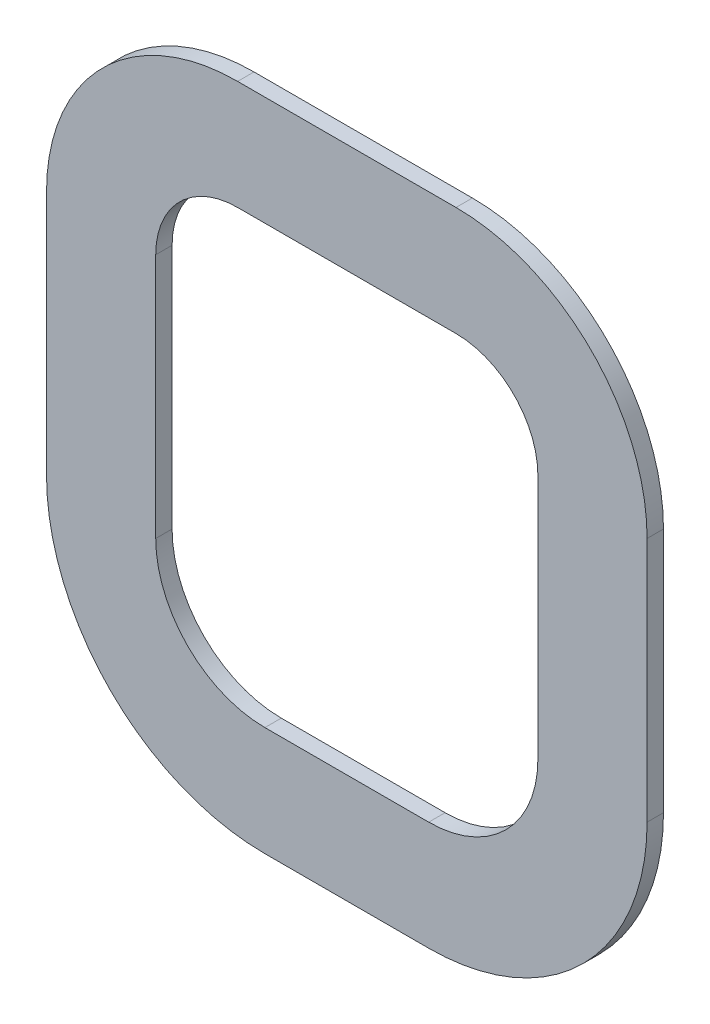
SolidWorks part; units mm, degrees
ref_plane "Front Plane" through (0, 0, 0) normal (0, 0, 1) x (1, 0, 0)
ref_plane "Top Plane" through (0, 0, 0) normal (0, 1, 0) x (1, 0, 0)
ref_plane "Right Plane" through (0, 0, 0) normal (1, 0, 0) x (0, 0, -1)
sketch "Sketch1" plane through (0, 0, 0) normal (0, 0, 1) x (1, 0, 0)
  line L0 (0, 52) -> (0, -68) construction
  line L1 (-55, 52) -> (55, 52) construction
  line L2 (-55, 52) -> (-55, -68) construction
  line L3 (-55, -68) -> (55, -68) construction
  line L4 (55, 52) -> (55, -68) construction
  line L5 (-20, 52) -> (20, 52)
  line L6 (-15, -68) -> (15, -68) construction
  line L7 (-55, 17) -> (55, 17) construction
  line L8 (-55, 17) -> (-55, -28)
  line L9 (-55, -28) -> (55, -28) construction
  line L10 (55, 17) -> (55, -28)
  line L11 (-0.5, -68) -> (0.5, -68) construction
  line L12 (-15, -68) -> (-0.5, -68)
  line L13 (0.5, -68) -> (15, -68)
  line L14 (-0.5, -68) -> (0.5, -68)
  line L15 (-20, 32) -> (20, 32)
  line L16 (35, 17) -> (35, -28)
  line L17 (0.5, -48) -> (15, -48)
  line L18 (-0.5, -48) -> (0.5, -48)
  line L19 (-15, -48) -> (-0.5, -48)
  line L20 (-35, 17) -> (-35, -28)
  arc A0 (-55, 17) -> (-20, 52) centre (-20, 17) cw
  arc A1 (20, 52) -> (55, 17) centre (20, 17) cw
  arc A2 (-55, -28) -> (-15, -68) centre (-15, -28) ccw
  arc A3 (15, -68) -> (55, -28) centre (15, -28) ccw
  arc A4 (-35, 17) -> (-20, 32) centre (-20, 17) cw
  arc A5 (20, 32) -> (35, 17) centre (20, 17) cw
  arc A6 (15, -48) -> (35, -28) centre (15, -28) ccw
  arc A7 (-35, -28) -> (-15, -48) centre (-15, -28) ccw
  point P9 (0, 52)
  point P18 (0, -68)
  point P22 (0, -68)
  dimension "D3" = 40
  dimension "D4" = 35
  dimension "D1" = 120
  dimension "D2" = 110
  dimension "D5" = 1
  dimension "D6" = 52
  dimension "D7" = 20
extrude "Boss-Extrude1" add sketch "Sketch1" along normal blind 3
